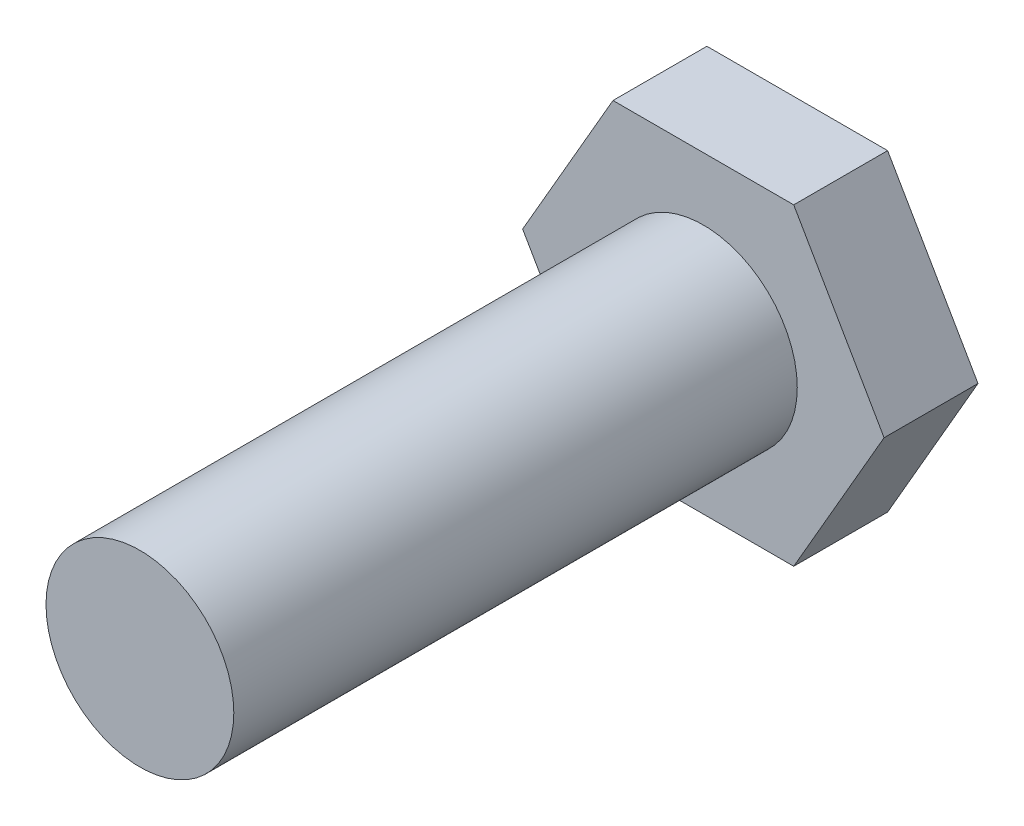
SolidWorks part; units mm, degrees
ref_plane "Front Plane" through (0, 0, 0) normal (0, 0, 1) x (1, 0, 0)
ref_plane "Top Plane" through (0, 0, 0) normal (0, 1, 0) x (1, 0, 0)
ref_plane "Right Plane" through (0, 0, 0) normal (1, 0, 0) x (0, 0, -1)
sketch "Sketch2" plane through (0, 0, 0) normal (0, 0, 1) x (1, 0, 0)
  line L1 (2.8868, 0) -> (1.4434, 2.5)
  line L2 (1.4434, 2.5) -> (-1.4434, 2.5)
  line L3 (-1.4434, 2.5) -> (-2.8868, 0)
  line L4 (-2.8868, 0) -> (-1.4434, -2.5)
  line L5 (-1.4434, -2.5) -> (1.4434, -2.5)
  line L6 (1.4434, -2.5) -> (2.8868, 0)
  circle A0 centre (0, 0) radius 2.5 construction
extrude "Boss-Extrude1" add sketch "Sketch2" along normal blind 1.5
sketch "Sketch3" plane through (0, 0, 1.5) normal (0, 0, 1) x (1, 0, 0)
  circle A0 centre (0, 0) radius 1.5
extrude "Boss-Extrude2" add sketch "Sketch3" along normal blind 9
